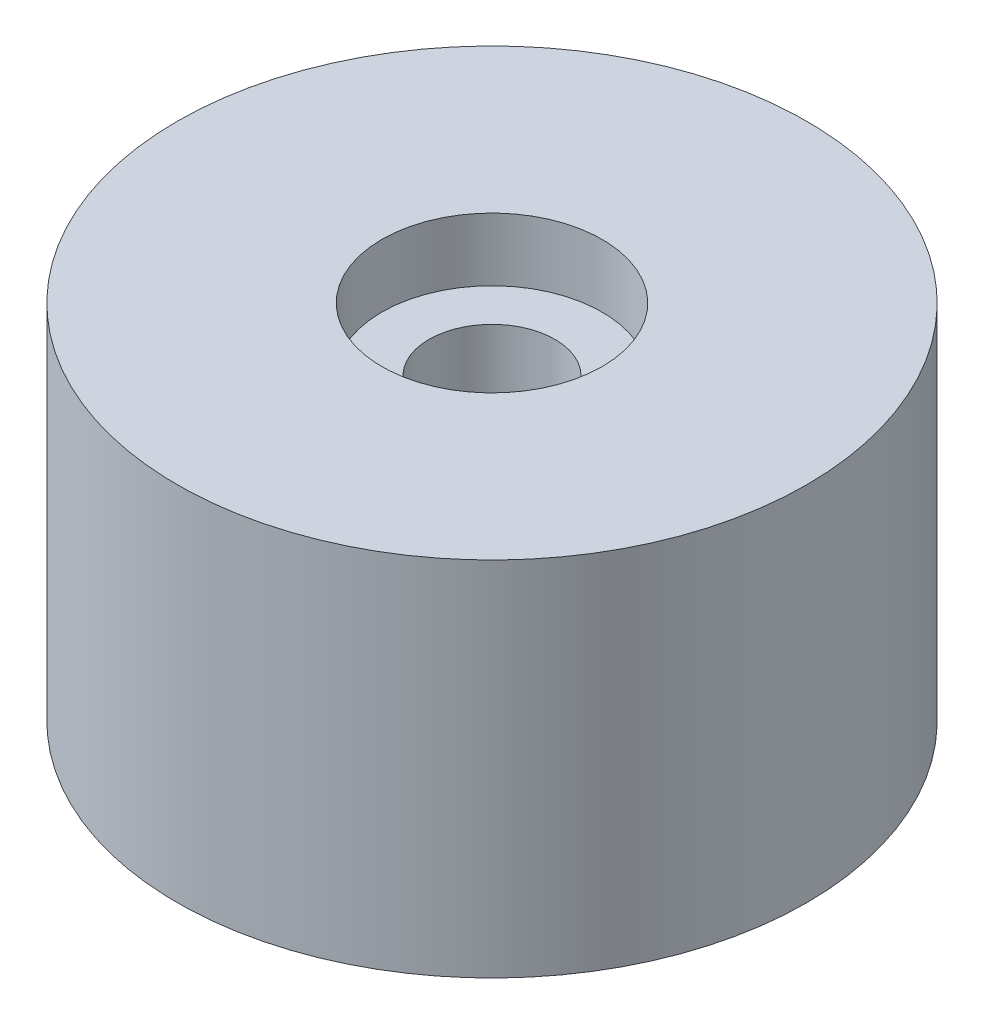
SolidWorks part; units mm, degrees
ref_plane "Front" through (0, 0, 0) normal (0, 0, 1) x (1, 0, 0)
ref_plane "Top" through (0, 0, 0) normal (0, 1, 0) x (1, 0, 0)
ref_plane "Right" through (0, 0, 0) normal (1, 0, 0) x (0, 0, -1)
sketch "Эскиз1" plane through (0, 0, 0) normal (0, 0, 1) x (1, 0, 0)
  line L0 (0, 3) -> (0, 0)
  line L1 (0, 0) -> (20, 0)
  line L2 (20, 0) -> (20, 23)
  line L3 (20, 23) -> (7, 23)
  line L4 (7, 23) -> (7, 19)
  line L5 (7, 19) -> (4, 19)
  line L6 (4, 19) -> (4, 3)
  line L7 (4, 3) -> (0, 3)
  point P0 (0, -0.5927)
  point P7 (0, 4.8628)
  dimension "D1" = 7
  dimension "D2" = 4
  dimension "D3" = 4
  dimension "D4" = 16
  dimension "D5" = 3
  dimension "D6" = 20
revolve "Повернуть1" add sketch "Эскиз1" angle 360 about L0
